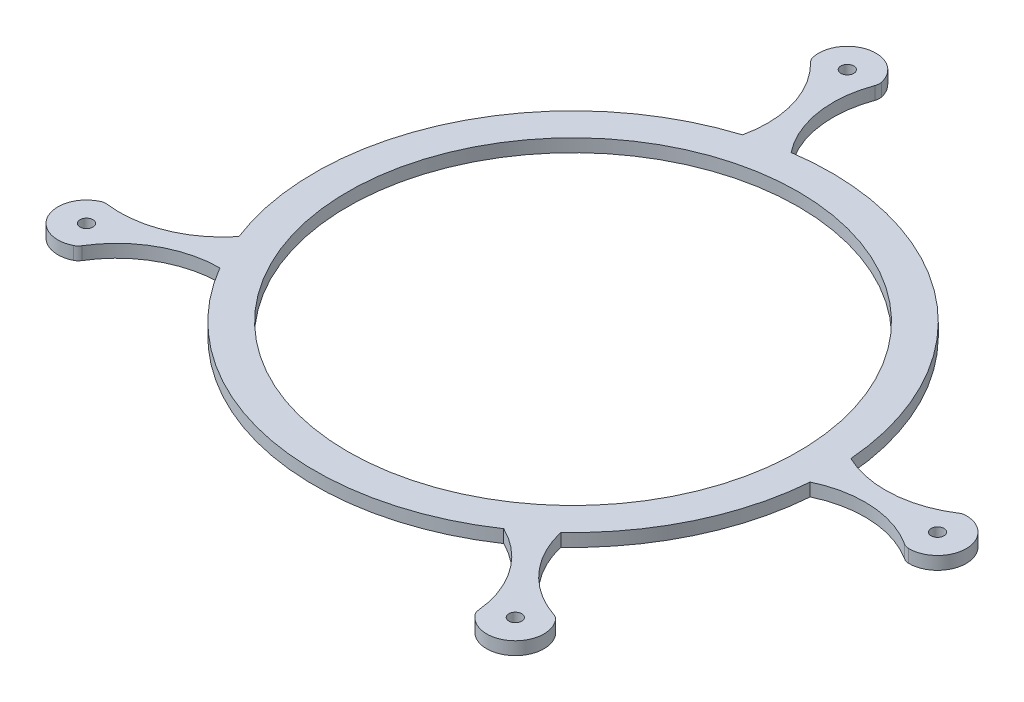
SolidWorks part; units mm, degrees
ref_plane "Front Plane" through (0, 0, 0) normal (0, 0, 1) x (1, 0, 0)
ref_plane "Top Plane" through (0, 0, 0) normal (0, 1, 0) x (1, 0, 0)
ref_plane "Right Plane" through (0, 0, 0) normal (1, 0, 0) x (0, 0, -1)
sketch "Sketch35" plane through (0, 0, 0) normal (0, 1, 0) x (1, 0, 0)
  arc A4 (72.6316, -196.7353) -> (72.6316, -182.6533) centre (72.7217, -189.6943) ccw
  arc A5 (71.2744, -196.3216) -> (72.6316, -196.7353) centre (72.6641, -194.1955) ccw
  arc A6 (72.6316, -182.6533) -> (71.2744, -183.067) centre (72.6641, -185.1931) ccw
  circle A7 centre (72.7217, -189.6943) radius 1.5875
  arc A8 (71.2744, -196.3216) -> (52.1409, -192.7486) centre (57.3787, -217.7169) ccw
  arc A9 (71.2744, -183.067) -> (52.1409, -186.6399) centre (57.3787, -161.6716) cw
  arc A10 (26.4703, -236.0732) -> (46.4003, -194.6881) centre (-16.903, -189.6943) ccw
  arc A11 (52.1409, -192.7486) -> (46.4003, -194.6881) centre (57.3787, -217.7169) ccw
  arc A12 (52.1409, -186.6399) -> (46.4003, -184.7005) centre (57.3787, -161.6716) cw
  arc A13 (33.416, -264.0853) -> (44.4258, -255.3052) centre (38.9771, -259.7657) ccw
  arc A14 (32.8933, -262.7662) -> (33.416, -264.0853) centre (35.422, -262.5271) ccw
  arc A15 (32.8933, -262.7662) -> (23.7572, -245.5793) centre (7.5019, -265.2419) ccw
  arc A16 (43.2562, -254.5021) -> (28.5331, -241.7706) centre (51.3199, -230.2982) cw
  arc A17 (44.4258, -255.3052) -> (43.2562, -254.5021) centre (42.4604, -256.9142) ccw
  arc A18 (28.5331, -241.7706) -> (26.4703, -236.0732) centre (51.3199, -230.2982) cw
  arc A19 (-26.1207, -252.5217) -> (18.6617, -242.3004) centre (-16.903, -189.6943) ccw
  arc A20 (23.7572, -245.5793) -> (18.6617, -242.3004) centre (7.5019, -265.2419) ccw
  arc A27 (-71.7706, -221.6598) -> (-26.1207, -252.5217) centre (-16.903, -189.6943) ccw
  arc A29 (-100.6259, -222.1981) -> (-94.5159, -234.8856) centre (-97.6521, -228.581) ccw
  arc A30 (-99.2236, -221.982) -> (-100.6259, -222.1981) centre (-99.5532, -224.5005) ccw
  arc A31 (-99.2236, -221.982) -> (-80.4346, -216.8994) centre (-95.987, -196.6764) ccw
  arc A32 (-93.4726, -233.924) -> (-77.7841, -222.4032) centre (-71.6699, -247.1714) cw
  arc A33 (-94.5159, -234.8856) -> (-93.4726, -233.924) centre (-95.6472, -232.6115) ccw
  arc A34 (-77.7841, -222.4032) -> (-71.7706, -221.6598) centre (-71.6699, -247.1714) cw
  arc A35 (-35.8579, -129.0893) -> (-76.1041, -212.6613) centre (-16.903, -189.6943) ccw
  arc A36 (-80.4346, -216.8994) -> (-76.1041, -212.6613) centre (-95.987, -196.6764) ccw
  arc A37 (-94.5159, -144.5029) -> (-100.6259, -157.1904) centre (-97.6521, -150.8076) ccw [skipped]
  arc A38 (-93.4726, -145.4645) -> (-94.5159, -144.5029) centre (-95.6472, -146.7771) ccw [skipped]
  arc A39 (-93.4726, -145.4645) -> (-77.7841, -156.9854) centre (-71.6699, -132.2171) ccw [skipped]
  arc A40 (-99.2236, -157.4066) -> (-80.4346, -162.4891) centre (-95.987, -182.7122) cw [skipped]
  arc A41 (-100.6259, -157.1904) -> (-99.2236, -157.4066) centre (-99.5532, -154.888) ccw [skipped]
  arc A42 (-80.4346, -162.4891) -> (-76.1041, -166.7273) centre (-95.987, -182.7122) cw [skipped]
  arc A44 (-77.7841, -156.9854) -> (-71.7706, -157.7287) centre (-71.6699, -132.2171) ccw [skipped]
  arc A45 (-29.9618, -100.8377) -> (-43.6908, -103.9713) centre (-36.8464, -102.3166) ccw
  arc A46 (-30.0632, -102.253) -> (-29.9618, -100.8377) centre (-32.4452, -101.3712) ccw
  arc A47 (-30.0632, -102.253) -> (-29.2889, -121.7018) centre (-6.1122, -111.0394) ccw
  arc A48 (-42.9855, -105.2024) -> (-35.2445, -123.0612) centre (-60.7523, -123.5106) cw
  arc A49 (-43.6908, -103.9713) -> (-42.9855, -105.2024) centre (-41.2219, -103.3744) ccw
  arc A50 (-35.2445, -123.0612) -> (-35.8579, -129.0893) centre (-60.7523, -123.5106) cw
  arc A51 (26.4703, -143.3153) -> (-26.1207, -126.8669) centre (-16.903, -189.6943) ccw
  arc A52 (-29.2889, -121.7018) -> (-26.1207, -126.8669) centre (-6.1122, -111.0394) ccw
  circle A59 centre (-16.903, -189.6943) radius 55.372
  arc A61 (46.4003, -184.7005) -> (26.4703, -143.3153) centre (-16.903, -189.6943) ccw
  circle A63 centre (-97.6521, -228.581) radius 1.5875
  circle A64 centre (-36.8464, -102.3166) radius 1.5875
  circle A66 centre (38.9771, -259.7657) radius 1.5875
  arc A67 (-35.2445, -256.3274) -> (-35.8579, -250.2992) centre (-60.7523, -255.8779) ccw [skipped]
  arc A68 (-29.2889, -257.6867) -> (-26.1207, -252.5217) centre (-6.1122, -268.3492) cw [skipped]
  arc A69 (-30.0632, -277.1356) -> (-29.2889, -257.6867) centre (-6.1122, -268.3492) cw [skipped]
  arc A70 (-42.9855, -274.1862) -> (-35.2445, -256.3274) centre (-60.7523, -255.8779) ccw [skipped]
  arc A71 (-43.6908, -275.4173) -> (-29.9618, -278.5508) centre (-36.8464, -277.0719) ccw [skipped]
  arc A72 (-42.9855, -274.1862) -> (-43.6908, -275.4173) centre (-41.2219, -276.0141) ccw [skipped]
  arc A73 (-29.9618, -278.5508) -> (-30.0632, -277.1356) centre (-32.4452, -278.0174) ccw [skipped]
  arc A74 (43.2562, -124.8865) -> (28.5331, -137.618) centre (51.3199, -149.0904) ccw [skipped]
  arc A75 (32.8933, -116.6223) -> (23.7572, -133.8093) centre (7.5019, -114.1467) cw [skipped]
  arc A76 (44.4258, -124.0833) -> (33.416, -115.3033) centre (38.9771, -119.6228) ccw [skipped]
  arc A77 (43.2562, -124.8865) -> (44.4258, -124.0833) centre (42.4604, -122.4744) ccw [skipped]
  arc A78 (33.416, -115.3033) -> (32.8933, -116.6223) centre (35.422, -116.8614) ccw [skipped]
  arc A79 (23.7572, -133.8093) -> (18.6617, -137.0881) centre (7.5019, -114.1467) cw [skipped]
  arc A80 (28.5331, -137.618) -> (26.4703, -143.3153) centre (51.3199, -149.0904) ccw [skipped]
  point P0 (0, 0)
  point P116 (-16.903, -189.6943)
  dimension "D1" = 63.5
  dimension "D3" = 110.744
  dimension "D4" = 3.175
  dimension "D2" = 7
extrude "Boss-Extrude5" add sketch "Sketch35" along normal blind 3.175
